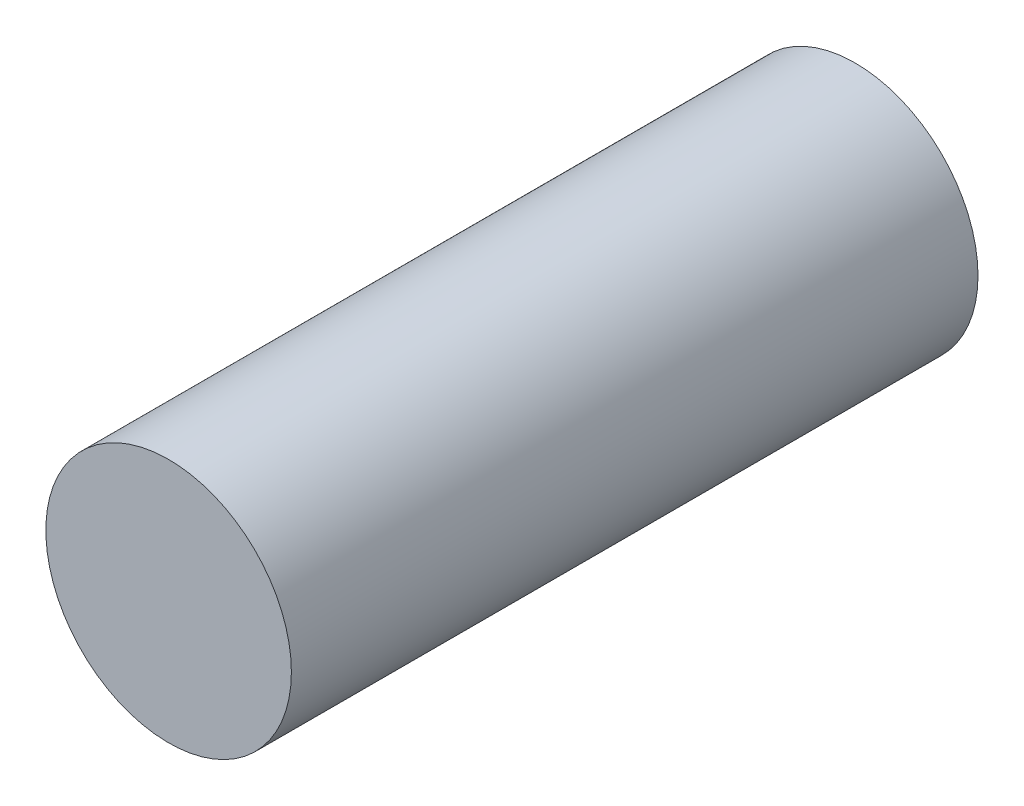
SolidWorks part; units mm, degrees
ref_plane "Front Plane" through (0, 0, 0) normal (0, 0, 1) x (1, 0, 0)
ref_plane "Top Plane" through (0, 0, 0) normal (0, 1, 0) x (1, 0, 0)
ref_plane "Right Plane" through (0, 0, 0) normal (1, 0, 0) x (0, 0, -1)
sketch "Sketch1" plane through (0, 0, 0) normal (0, 0, 1) x (1, 0, 0)
  circle A0 centre (0, 0) radius 109
  circle A1 centre (0, 0) radius 100.2
  dimension "D1" = 218
  dimension "D2" = 8.8
extrude "Boss-Extrude1" add sketch "Sketch1" along normal blind 609.6
sketch "Sketch2" plane through (0, 0, 0) normal (0, 0, -1) x (-1, 0, 0)
  circle A0 centre (0, 0) radius 100.2
extrude "Boss-Extrude2" add sketch "Sketch2" against normal up to surface (609.6 mm away) up to face at (109, 0, 609.6)
